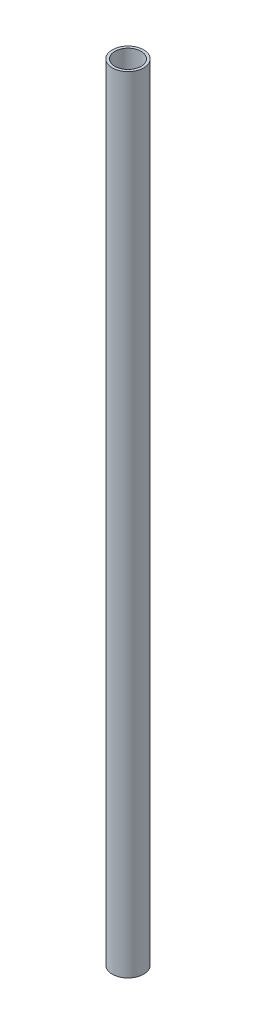
SolidWorks part; units mm, degrees
material "1060 Alloy"
ref_plane "Front Plane" through (0, 0, 0) normal (0, 0, 1) x (1, 0, 0)
ref_plane "Top Plane" through (0, 0, 0) normal (0, 1, 0) x (1, 0, 0)
ref_plane "Right Plane" through (0, 0, 0) normal (1, 0, 0) x (0, 0, -1)
sketch "Sketch1" plane through (0, 0, 0) normal (0, 1, 0) x (1, 0, 0)
  circle A0 centre (0, 0) radius 6
  circle A1 centre (0, 0) radius 5
extrude "Boss-Extrude1" add sketch "Sketch1" along normal blind 300
